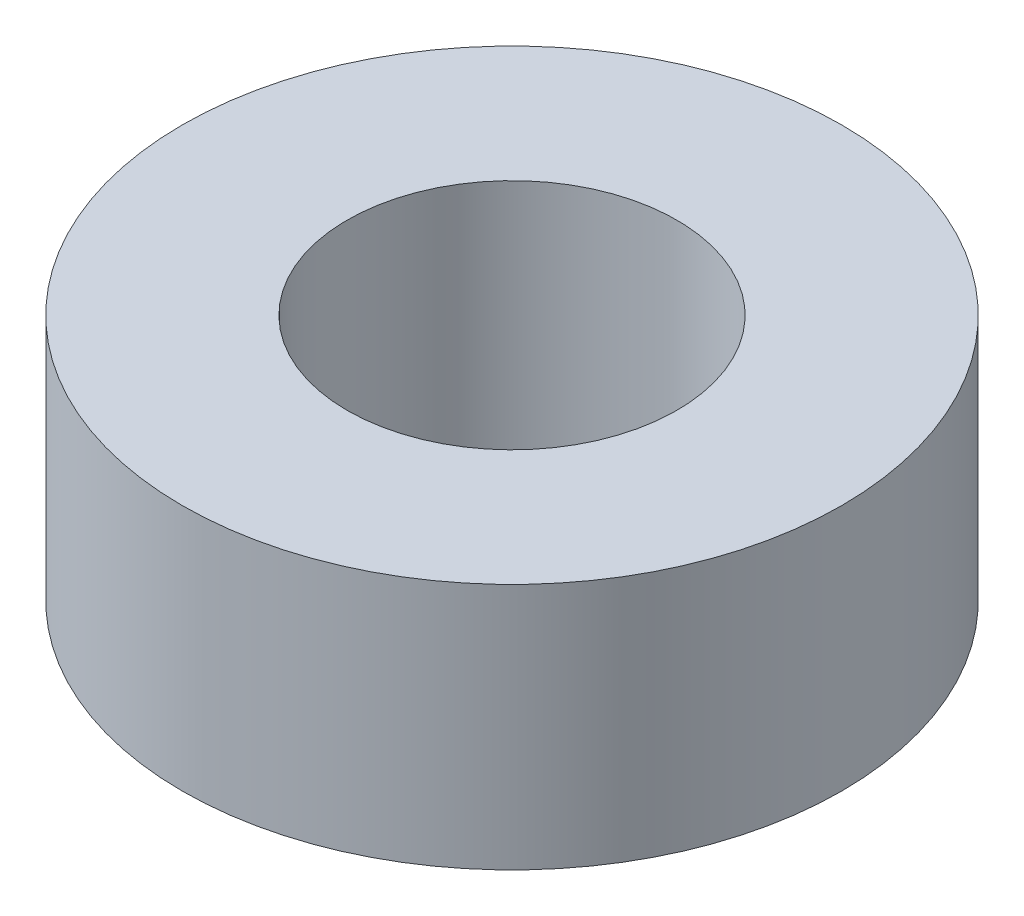
SolidWorks part; units mm, degrees
material "1023 Carbon Steel Sheet (SS)"
ref_plane "Front Plane" through (0, 0, 0) normal (0, 0, 1) x (1, 0, 0)
ref_plane "Top Plane" through (0, 0, 0) normal (0, 1, 0) x (1, 0, 0)
ref_plane "Right Plane" through (0, 0, 0) normal (1, 0, 0) x (0, 0, -1)
sketch "Sketch1" plane through (0, 0, 0) normal (0, 1, 0) x (1, 0, 0)
  circle A0 centre (0, 0) radius 10
  circle A1 centre (0, 0) radius 20
  dimension "D1" = 20
  dimension "D2" = 40
extrude "Boss-Extrude1" add sketch "Sketch1" along normal blind 15
